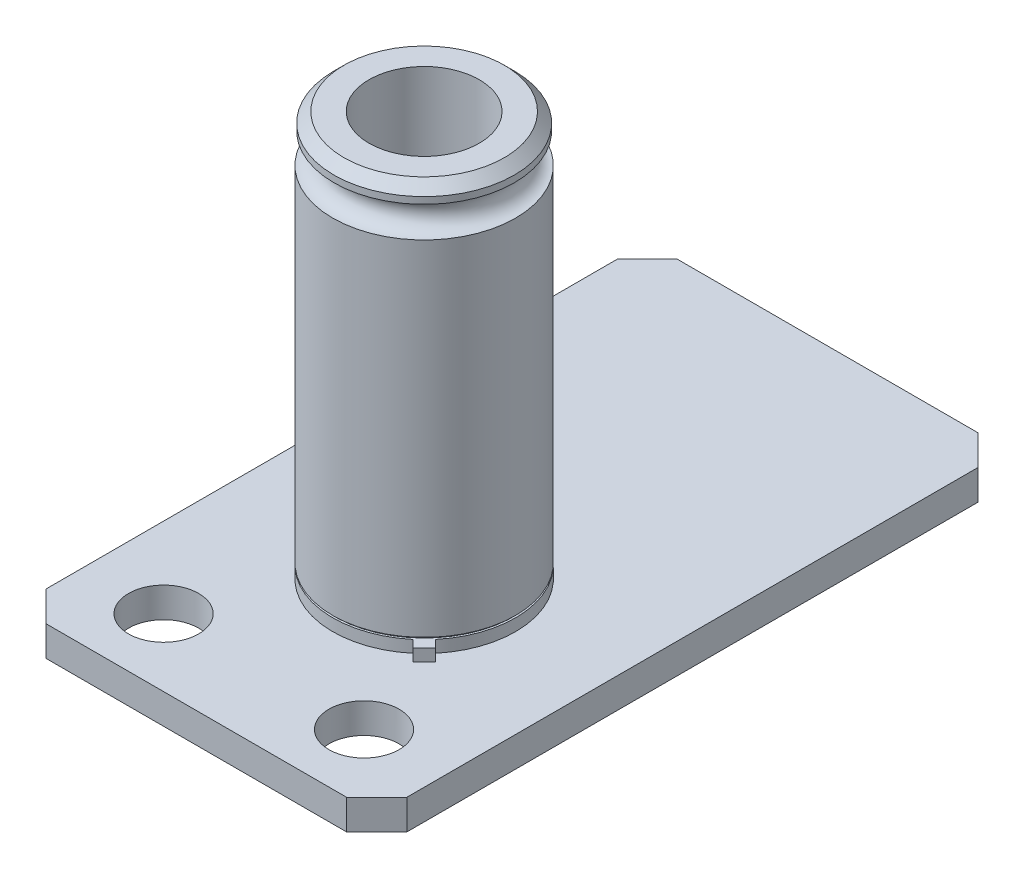
SolidWorks part; units mm, degrees
ref_plane "Piano frontale" through (0, 0, 0) normal (0, 0, 1) x (1, 0, 0)
ref_plane "Piano superiore" through (0, 0, 0) normal (0, 1, 0) x (1, 0, 0)
ref_plane "Piano destro" through (0, 0, 0) normal (1, 0, 0) x (0, 0, -1)
sketch "Schizzo1" plane through (0, 0, 0) normal (0, 1, 0) x (1, 0, 0)
  circle A0 centre (0, 0) radius 4.56
  dimension "D1" = 9.12
extrude "Estrusione-Estrusione1" add sketch "Schizzo1" along normal blind 19.5
sketch "Schizzo2" plane through (0, 0, 0) normal (0, 0, 1) x (1, 0, 0)
  line L0 (-4.56, 19.5) -> (-4.56, 0) construction
  line L1 (4.56, 19.5) -> (-4.56, 19.5) construction
  line L2 (0, 19.5) -> (0, 15.6496) construction
  circle A0 centre (-4.56, 17.92) radius 0.75
  dimension "D1" = 1.5
  dimension "D2" = 1.58
revolve "Taglia-Rivoluzione1" cut sketch "Schizzo2" angle 360 about L2
sketch "Schizzo3" plane through (0, 0, 0) normal (0, 0, 1) x (1, 0, 0)
  line L0 (0, 19.5) -> (0, 17.17) construction
  line L1 (-6.8929, 18.2289) -> (-4.5, 18.2289)
  line L2 (-6.8929, 18.2289) -> (-6.8929, 19.7375)
  line L3 (-6.8929, 19.7375) -> (-4.5, 19.7375)
  line L4 (-4.5, 18.2289) -> (-4.5, 19.7375)
  line L5 (-6.8929, 18.2289) -> (-4.5, 19.7375) construction
  line L6 (-6.8929, 19.7375) -> (-4.5, 18.2289) construction
  line L7 (4.56, 19.5) -> (-4.56, 19.5) construction
  line L8 (-4.56, 17.17) -> (4.56, 17.17) construction
  point P0 (-5.6964, 18.9832)
  dimension "D1" = 4.5
revolve "Taglia-Rivoluzione2" cut sketch "Schizzo3" angle 360 about L0
chamfer "Smusso1" distance 0.5 angle 45 1 edges at (0, 19.5, 4.5)
sketch "Schizzo4" plane through (0, 19.5, 0) normal (0, 1, 0) x (1, 0, 0)
  line L0 (0, 0) -> (4, 0)
  circle A0 centre (0, 0) radius 4 construction
hole_wizard "Foro per Vite M5-1" positions "Schizzo3D1" profile "Schizzo5" hole size "M5" standard "ISO" end condition up to next
sketch3d "Schizzo3D1"
  point P0 (0, 19.5, 0)
sketch "Schizzo5" plane through (0, 19.5, 0) normal (1, 0, 0) x (0, 0, 1)
  line L0 (0, 0) -> (0, 19.5)
  line L1 (0, 19.5) -> (2.75, 19.5)
  line L2 (2.75, 19.5) -> (2.75, 0)
  line L5 (2.75, 0) -> (0, 0)
  line L11 (0, -6.35) -> (0, 107.95) construction
  dimension "Thru Hole Dia." = 5.5
  dimension "Thru Hole Depth" = 19.5
cosmetic thread "Filettatura cosmetica1" parameters "D2"=16.5
sketch "Schizzo7" plane through (0, 0, 0) normal (0, 0, 1) x (1, 0, 0)
  line L0 (0, 0) -> (0, -0.7)
  line L1 (0, -0.7) -> (-4.56, -0.7)
  line L2 (-4.56, -0.7) -> (-4.56, -0.1)
  line L3 (-4.56, -0.1) -> (-4.46, -0.1)
  line L4 (-4.46, -0.1) -> (-4.46, 0)
  line L5 (-4.56, 0) -> (4.56, 0) construction
  line L6 (-4.46, 0) -> (0, 0)
  line L7 (0, 19.5) -> (4, 19.5) construction
  line L8 (-4.56, 17.17) -> (-4.56, 0) construction
  dimension "D1" = 20.2
  dimension "D2" = 0.1
  dimension "D3" = 0.1
revolve "Rivoluzione1" add sketch "Schizzo7" angle 360 about L0
sketch "Schizzo8" plane through (0, -0.7, 0) normal (0, -1, 0) x (1, 0, 0)
  line L0 (0, 0) -> (3.578, 3.578) construction
  line L1 (0, 0) -> (4, 0) construction
  line L2 (0.2828, -0.2828) -> (3.8608, 3.2951)
  line L3 (-0.2828, 0.2828) -> (3.2951, 3.8608)
  line L4 (3.8608, 3.2951) -> (3.578, 3.578)
  line L5 (3.578, 3.578) -> (3.2951, 3.8608)
  line L6 (-0.2828, 0.2828) -> (0.2828, -0.2828)
  line L7 (3.2244, 3.2244) -> (4.0701, 2.3787) construction
  circle A0 centre (0, 0) radius 4.56 construction
  dimension "D1" = 45
  dimension "D4" = 0.5
  dimension "D2" = 0.4
  dimension "D3" = 0.4
extrude "Estrusione-Estrusione2" add sketch "Schizzo8" against normal up to surface (0.6 mm away) up to face at (-4.56, -0.1, 0)
sketch "Schizzo9" plane through (0, -0.7, 0) normal (0, -1, 0) x (1, 0, 0)
  circle A0 centre (0, 0) radius 2.54 construction
  circle A1 centre (0, 2.54) radius 0.8 construction
  circle A2 centre (2.54, 0) radius 0.8
  circle A3 centre (0, -2.54) radius 0.8
  circle A4 centre (-2.54, 0) radius 0.8
  dimension "D1" = 5.08
  dimension "D2" = 1.6
extrude "Taglio-Estrusione1" cut sketch "Schizzo9" against normal up to surface (0.6 mm away) up to face at (1.7859, -0.1, 1.7859)
sketch "Schizzo10" plane through (0, -0.1, 0) normal (0, -1, 0) x (1, 0, 0)
  circle A0 centre (0, 0) radius 2.54 construction
  circle A1 centre (0, 2.54) radius 0.225
  circle A2 centre (2.54, 0) radius 0.225
  circle A3 centre (0, -2.54) radius 0.225
  circle A4 centre (-2.54, 0) radius 0.225
  dimension "D1" = 0.45
extrude "Estrusione-Estrusione3" add sketch "Schizzo10" along normal blind 13
ref_plane "Düzlem1" through (0, 0, 0) normal (0.7071, 0, -0.7071) x (-0.5774, -0.5774, -0.5774)
sketch "Çizim1" plane through (0, -0.7, 0) normal (0, -1, 0) x (-1, 0, 0)
  line L0 (0, 20.1329) -> (0, -11.0395) construction
  line L2 (-9, 11.3671) -> (-9, -11.3671)
  line L3 (-9, -11.3671) -> (9, -11.3671)
  line L4 (9, 14.7227) -> (9, -11.3671)
  line L8 (9, 14.7227) -> (9, 20.1329)
  line L9 (9, 20.1329) -> (-9, 20.1329)
  line L10 (-9, 11.3671) -> (-9, 20.1329)
  point P0 (0, 0)
  point P10 (0, 0)
  dimension "D1" = 18
  dimension "D2" = 31.5
extrude "Yükseklik-Ekstrüzyon1" add sketch "Çizim1" along normal blind 1.5
sketch "Çizim2" plane through (-9, 0, 0) normal (-1, 0, 0) x (0, 0, 1)
  line L1 (-2.9333, -2.4376) -> (3.5096, -2.4376)
  line L2 (-2.9333, -2.4376) -> (-2.9333, -13.3327)
  line L3 (-2.9333, -13.3327) -> (3.5096, -13.3327)
  line L4 (3.5096, -2.4376) -> (3.5096, -13.3327)
extrude "Kes-Ekstrüzyon1" cut sketch "Çizim2" against normal blind 13.5
sketch "Çizim3" plane through (0, -0.7, 0) normal (0, 1, 0) x (1, 0, 0)
  circle A0 centre (-5, -8) radius 1.75
  circle A1 centre (5, -8) radius 1.75
  point P4 (0, 0)
  dimension "D1" = 10
  dimension "D2" = 5
  dimension "D3" = 3.5
  dimension "D4" = 8
extrude "Kes-Ekstrüzyon2" cut sketch "Çizim3" against normal blind 13.5
sketch "Çizim4" plane through (0, -0.7, 0) normal (0, 1, 0) x (1, 0, 0)
  line L0 (-9, -9.8671) -> (-7.5, -11.3671)
  line L1 (-9, -11.3671) -> (-9, 20.1329) construction
  line L2 (9, -11.3671) -> (-9, -11.3671) construction
  line L3 (-7.5, -11.3671) -> (-9, -11.3671)
  line L4 (-9, -11.3671) -> (-9, -9.8671)
  line L5 (0, 0) -> (0, -7.1227) construction
  line L6 (9, -11.3671) -> (9, -9.8671)
  line L7 (7.5, -11.3671) -> (9, -11.3671)
  line L8 (9, -9.8671) -> (7.5, -11.3671)
  line L9 (-9, 4.3829) -> (9, 4.3829) construction
  line L10 (9, 20.1329) -> (9, -11.3671) construction
  line L11 (9, 18.6329) -> (7.5, 20.1329)
  line L12 (7.5, 20.1329) -> (9, 20.1329)
  line L13 (9, 20.1329) -> (9, 18.6329)
  line L14 (-9, 20.1329) -> (-9, 18.6329)
  line L15 (-7.5, 20.1329) -> (-9, 20.1329)
  line L16 (-9, 18.6329) -> (-7.5, 20.1329)
  dimension "D1" = 1.5
  dimension "D2" = 1.5
extrude "Kes-Ekstrüzyon3" cut sketch "Çizim4" against normal blind 13.5
